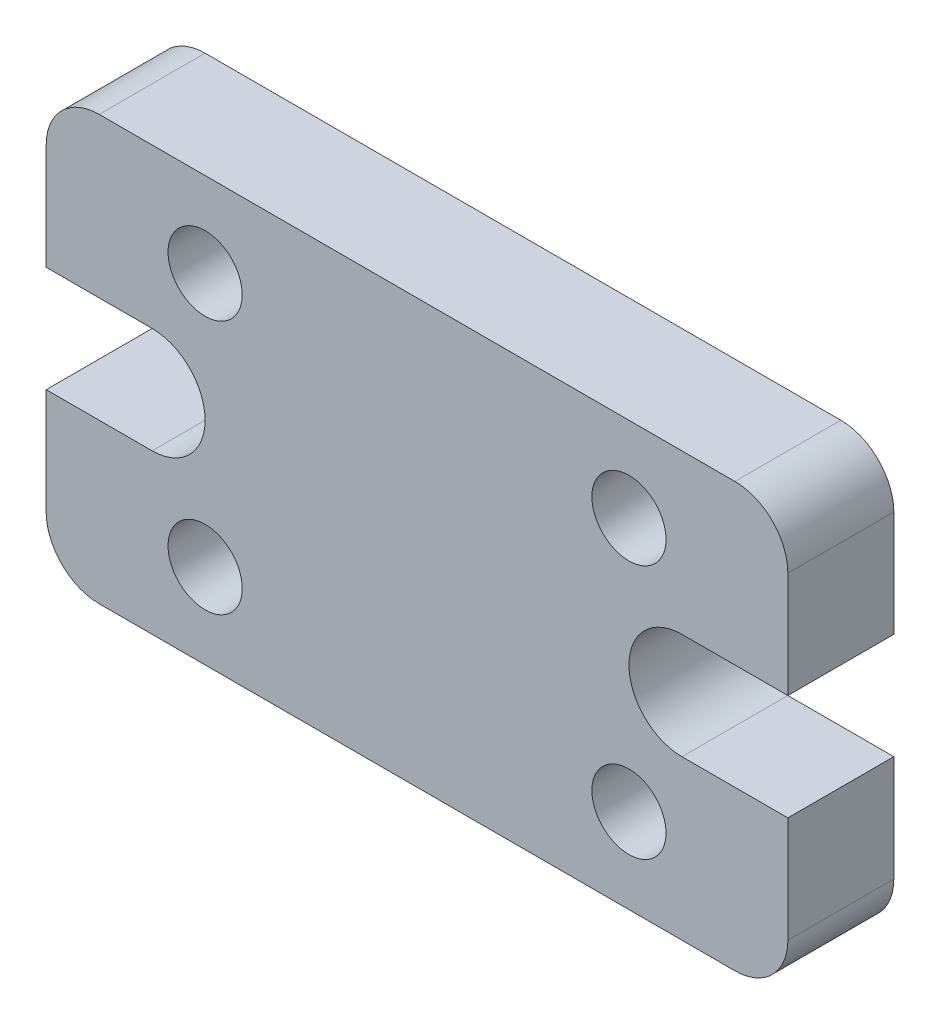
SolidWorks part; units mm, degrees
ref_plane "Alzado" through (0, 0, 0) normal (0, 0, 1) x (1, 0, 0)
ref_plane "Planta" through (0, 0, 0) normal (0, 1, 0) x (1, 0, 0)
ref_plane "Vista lateral" through (0, 0, 0) normal (1, 0, 0) x (0, 0, -1)
sketch "Croquis1" plane through (0, 0, 0) normal (0, 0, 1) x (1, 0, 0)
  line L0 (0, 52.9978) -> (0, 0) construction
  line L1 (0, 0) -> (69.9623, 0) construction
  line L2 (-30, 20) -> (30, 20)
  line L3 (35, 15) -> (35, 5)
  line L4 (35, 5) -> (25, 5)
  line L5 (-35, 5) -> (-25, 5)
  line L6 (-35, 15) -> (-35, 5)
  line L7 (35, -15) -> (35, -5)
  line L8 (35, -5) -> (25, -5)
  line L9 (-35, -5) -> (-25, -5)
  line L10 (-35, -15) -> (-35, -5)
  line L11 (-30, -20) -> (30, -20)
  arc A0 (30, 20) -> (35, 15) centre (30, 15) cw
  arc A1 (25, 5) -> (25, -5) centre (25, 0) ccw
  arc A2 (-25, 5) -> (-25, -5) centre (-25, 0) cw
  arc A3 (-30, 20) -> (-35, 15) centre (-30, 15) ccw
  arc A4 (30, -20) -> (35, -15) centre (30, -15) ccw
  arc A5 (-30, -20) -> (-35, -15) centre (-30, -15) cw
  circle A6 centre (20, 12) radius 3.5
  circle A7 centre (20, -12) radius 3.5
  circle A8 centre (-20, -12) radius 3.5
  circle A9 centre (-20, 12) radius 3.5
  point P19 (0, 20)
  dimension "D4" = 5
  dimension "D5" = 5
  dimension "D6" = 7
  dimension "D1" = 50
  dimension "D2" = 70
  dimension "D3" = 40
  dimension "D7" = 12
  dimension "D8" = 40
extrude "Saliente-Extruir2" add sketch "Croquis1" along normal blind 10
